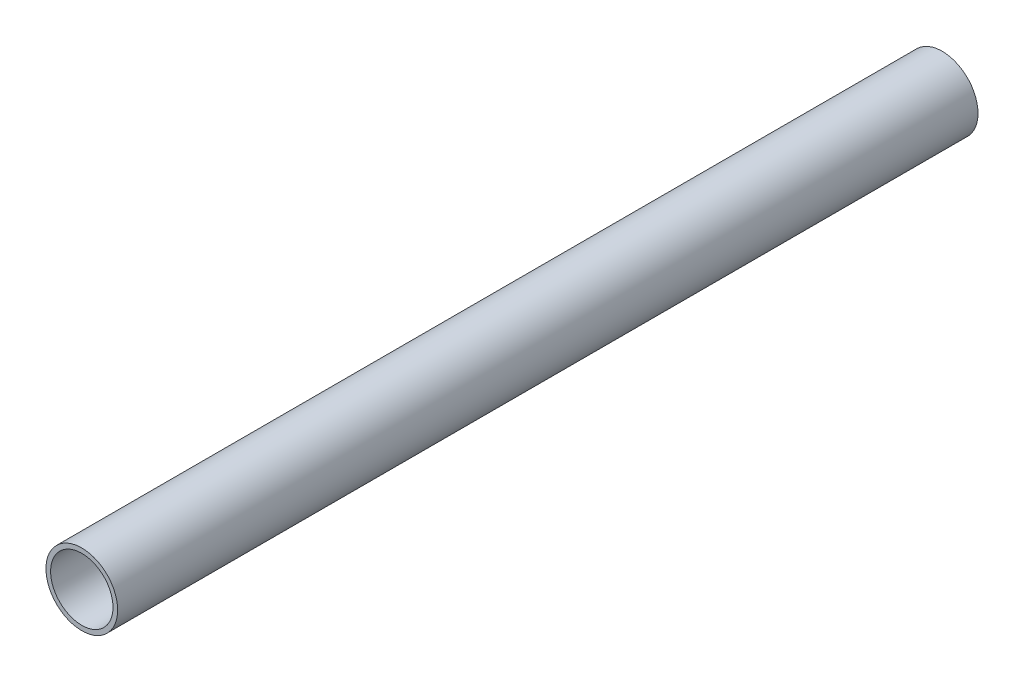
SolidWorks part; units mm, degrees
ref_plane "Front Plane" through (0, 0, 0) normal (0, 0, 1) x (1, 0, 0)
ref_plane "Top Plane" through (0, 0, 0) normal (0, 1, 0) x (1, 0, 0)
ref_plane "Right Plane" through (0, 0, 0) normal (1, 0, 0) x (0, 0, -1)
sketch "Sketch1" plane through (0, 0, 0) normal (0, 0, 1) x (1, 0, 0)
  line L0 (12.7, 0) -> (11.049, 0) construction
  line L1 (-12.7, 0) -> (12.7, 0) construction
  dimension "OD" = 25.4
  dimension "Wall Thickness" = 1.651
sketch "Sketch2" plane through (0, 0, 0) normal (1, 0, 0) x (0, 0, -1)
  line L0 (152.4, 0) -> (-152.4, 0)
  point P4 (0, 0)
  dimension "Length" = 304.8
sketch "Sketch3" plane through (0, 0, 0) normal (0, 0, 1) x (1, 0, 0)
  circle A0 centre (0, 0) radius 12.7
  circle A1 centre (0, 0) radius 11.049
extrude "Boss-Extrude1" add sketch "Sketch3" along normal up to vertex (152.4 mm away) and the other way up to vertex (152.4 mm away) up to point (0, 0, 152.4) other way up to point (0, 0, -152.4)
